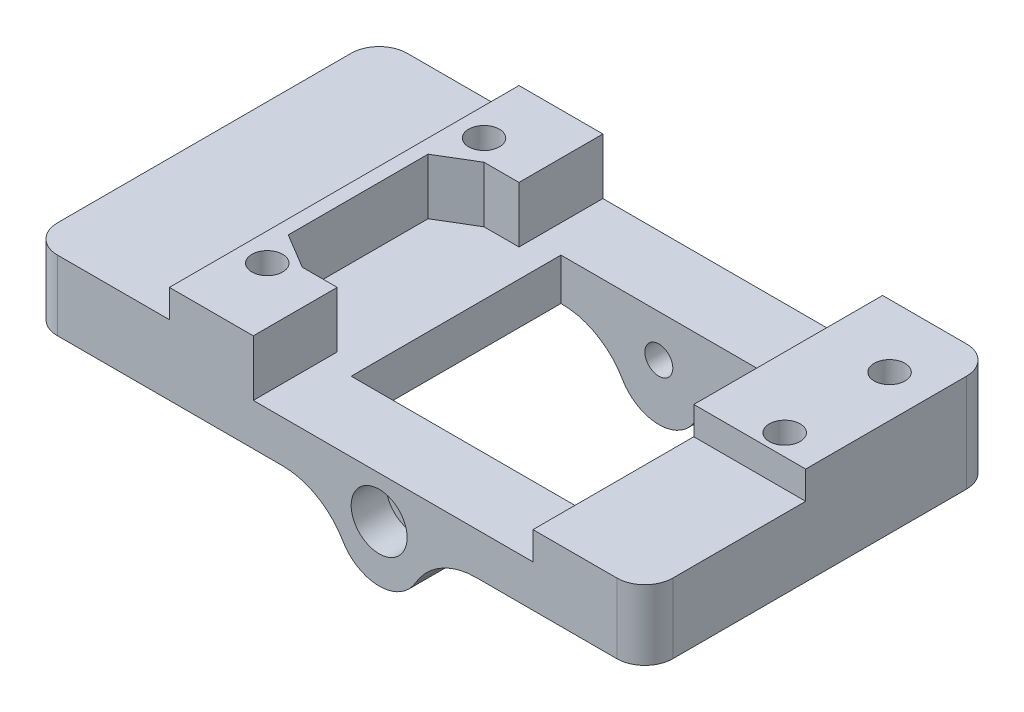
SolidWorks part; units mm, degrees
ref_plane "前视基准面" through (0, 0, 0) normal (0, 0, 1) x (1, 0, 0)
ref_plane "上视基准面" through (0, 0, 0) normal (0, 1, 0) x (1, 0, 0)
ref_plane "右视基准面" through (0, 0, 0) normal (1, 0, 0) x (0, 0, -1)
sketch "草图1" plane through (0, 0, 0) normal (0, 1, 0) x (1, 0, 0)
  line L1 (-25, -12.5) -> (25, -12.5)
  line L2 (-25, -12.5) -> (-25, 12.5)
  line L3 (-25, 12.5) -> (25, 12.5)
  line L4 (25, -12.5) -> (25, 12.5)
  line L5 (-25, -12.5) -> (25, 12.5) construction
  line L6 (-25, 12.5) -> (25, -12.5) construction
  point P0 (0, 0)
  dimension "D1" = 25
  dimension "D2" = 50
extrude "凸台-拉伸1" add sketch "草图1" along normal blind 7
sketch "草图2" plane through (0, 0, 12.5) normal (0, 0, 1) x (1, 0, 0)
  line L0 (-25, 0) -> (25, 0) construction
  line L3 (-25, 7) -> (-25, 0) construction
  line L4 (0, -0.7454) -> (0, 2.7804) construction
  line L8 (-25, 0) -> (25, 0)
  line L9 (25, 0) -> (25, 7)
  line L10 (25, 7) -> (-25, 7)
  line L11 (-25, 7) -> (-25, 0)
  line L12 (-2.8284, 0) -> (2.8284, 0)
  arc A0 (-2.8284, 0) -> (2.8284, 0) centre (0, -1) ccw
  dimension "D1" = 3
  dimension "D2" = 25
  dimension "D4" = 1
  dimension "D3" = 0
extrude "凸台-拉伸2" add sketch "草图2" against normal blind 5
sketch "草图3" plane through (0, 0, 12.5) normal (0, 0, 1) x (1, 0, 0)
  line L0 (0, -200000.7454) -> (0, 200002.7804) construction
  line L1 (-25, 7) -> (25, 7) construction
  circle A0 centre (0, 0) radius 1
  dimension "D1" = 2
  dimension "D2" = 7
extrude "切除-拉伸1" cut sketch "草图3" against normal through all
mirror "镜向1" about plane through (0, 0, 0) normal (0, 0, 1) of "切除-拉伸1", "凸台-拉伸2"
sketch "草图5" plane through (0, 7, 0) normal (0, 1, 0) x (1, 0, 0)
  line L0 (-5.5, 0) -> (5.5, 0) construction
  line L1 (25, 12.5) -> (19, 12.5)
  line L2 (25, 12.5) -> (25, -12.5)
  line L3 (25, -12.5) -> (19, -12.5)
  line L4 (19, 12.5) -> (19, -12.5)
  line L5 (25, 12.5) -> (19, -12.5) construction
  line L6 (25, -12.5) -> (19, 12.5) construction
  line L7 (-25, -12.5) -> (25, -12.5) construction
  line L8 (25, -12.5) -> (25, 12.5) construction
  point P0 (22, 0)
  dimension "D1" = 6
extrude "切除-拉伸5" cut sketch "草图5" against normal through all
sketch "草图6" plane through (0, 0, 12.5) normal (0, 0, 1) x (1, 0, 0)
  circle A0 centre (0, 0) radius 2
  dimension "D1" = 4
extrude "切除-拉伸6" cut sketch "草图6" against normal blind 2.5
fillet "圆角2" radius 2 4 edges at (-25, 3.5, -12.5) (-25, 3.5, 12.5) (19, 3.5, 12.5) (19, 3.5, -12.5)
fillet "圆角3" radius 5 4 edges at (-2.8284, 0, 10) (2.8284, 0, 10) (2.8284, 0, -10) (-2.8284, 0, -10)
sketch "草图8" plane through (0, 7, 0) normal (0, 1, 0) x (1, 0, 0)
  line L0 (17, 12.5) -> (-23, 12.5) construction
  line L2 (-25, 10.5) -> (-25, -10.5) construction
  circle A0 centre (-13, 8) radius 1.1
  circle A1 centre (-13, -7.5) radius 1.1
  circle A2 centre (16, 8) radius 1.1
  circle A3 centre (16, 0.5) radius 1.1
  dimension "D1" = 2.2
  dimension "D2" = 4.5
  dimension "D3" = 12
  dimension "D4" = 15.5
  dimension "D5" = 29
  dimension "D6" = 7.5
extrude "切除-拉伸9" cut sketch "草图8" against normal through all
sketch "草图4" plane through (0, 7, 0) normal (0, 1, 0) x (1, 0, 0)
  line L0 (-5.5, 0) -> (5.5, 0) construction
  line L1 (-9, -12.5) -> (11, -12.5)
  line L2 (-9, -12.5) -> (-9, -6.5)
  line L3 (-9, 12.5) -> (11, 12.5)
  line L4 (11, -12.5) -> (11, 12.5)
  line L5 (-9, -12.5) -> (11, 12.5) construction
  line L6 (-9, 12.5) -> (11, -12.5) construction
  line L7 (17, 12.5) -> (-23, 12.5) construction
  line L8 (-9, -6.5) -> (-11.5, -6.5)
  line L9 (-11.5, -6.5) -> (-14, -5)
  line L10 (-25, 10.5) -> (-25, -10.5) construction
  line L11 (-14, -5) -> (-14, 5)
  line L12 (-9, 0) -> (-50009, 0) construction
  line L13 (-9, 6.5) -> (-11.5, 6.5)
  line L14 (-11.5, 6.5) -> (-14, 5)
  line L15 (-9, 6.5) -> (-9, 12.5)
  point P0 (1, 0)
  point P19 (-14, 0)
  dimension "D1" = 20
  dimension "D2" = 16
  dimension "D3" = 2.5
  dimension "D4" = 6.5
  dimension "D5" = 5
  dimension "D6" = 10
extrude "切除-拉伸4" cut sketch "草图4" against normal blind 4
sketch "草图7" plane through (0, 3, 0) normal (0, 1, 0) x (1, 0, 0)
  line L0 (-5.5, 0) -> (5.5, 0) construction
  line L1 (11, -12.5) -> (11, 12.5) construction
  line L2 (-7, 7.5) -> (9, 7.5)
  line L3 (-7, 7.5) -> (-7, -7.5)
  line L4 (-7, -7.5) -> (9, -7.5)
  line L5 (9, 7.5) -> (9, -7.5)
  line L6 (-7, 7.5) -> (9, -7.5) construction
  line L7 (-7, -7.5) -> (9, 7.5) construction
  point P2 (1, 0)
  dimension "D1" = 15
  dimension "D2" = 10
  dimension "D3" = 16
extrude "切除-拉伸7" cut sketch "草图7" against normal through all
sketch "草图10" plane through (0, 0, 0) normal (0, -1, 0) x (1, 0, 0)
  line L0 (5.5, 0) -> (-5.5, 0) construction
  line L1 (-25, -10.5) -> (-25, 10.5) construction
  circle A0 centre (-20, 0) radius 3
  dimension "D1" = 6
  dimension "D2" = 5
extrude "切除-拉伸11" cut sketch "草图10" against normal blind 3
sketch "草图12" plane through (0, 3, 0) normal (0, -1, 0) x (1, 0, 0)
  circle A0 centre (-20, 0) radius 2
  dimension "D1" = 4
extrude "凸台-拉伸3" add sketch "草图12" along normal blind 5
sketch "草图13" plane through (0, 7, 0) normal (0, 1, 0) x (1, 0, 0)
  line L0 (-23, -12.5) -> (-9, -12.5) construction
  line L1 (-15, 12.5) -> (-25, 12.5)
  line L2 (-15, 12.5) -> (-15, -12.5)
  line L3 (-15, -12.5) -> (-25, -12.5)
  line L4 (-25, 12.5) -> (-25, -12.5)
  line L5 (-25, 10.5) -> (-25, -10.5) construction
  line L6 (-9, 12.5) -> (-23, 12.5) construction
  line L7 (19, 10.5) -> (19, -10.5) construction
  line L8 (11, -12.5) -> (19, -12.5)
  line L9 (11, -12.5) -> (11, -1)
  line L10 (11, -1) -> (19, -1)
  line L11 (19, -12.5) -> (19, -1)
  dimension "D1" = 10
  dimension "D2" = 11.5
extrude "切除-拉伸12" cut sketch "草图13" against normal blind 2
